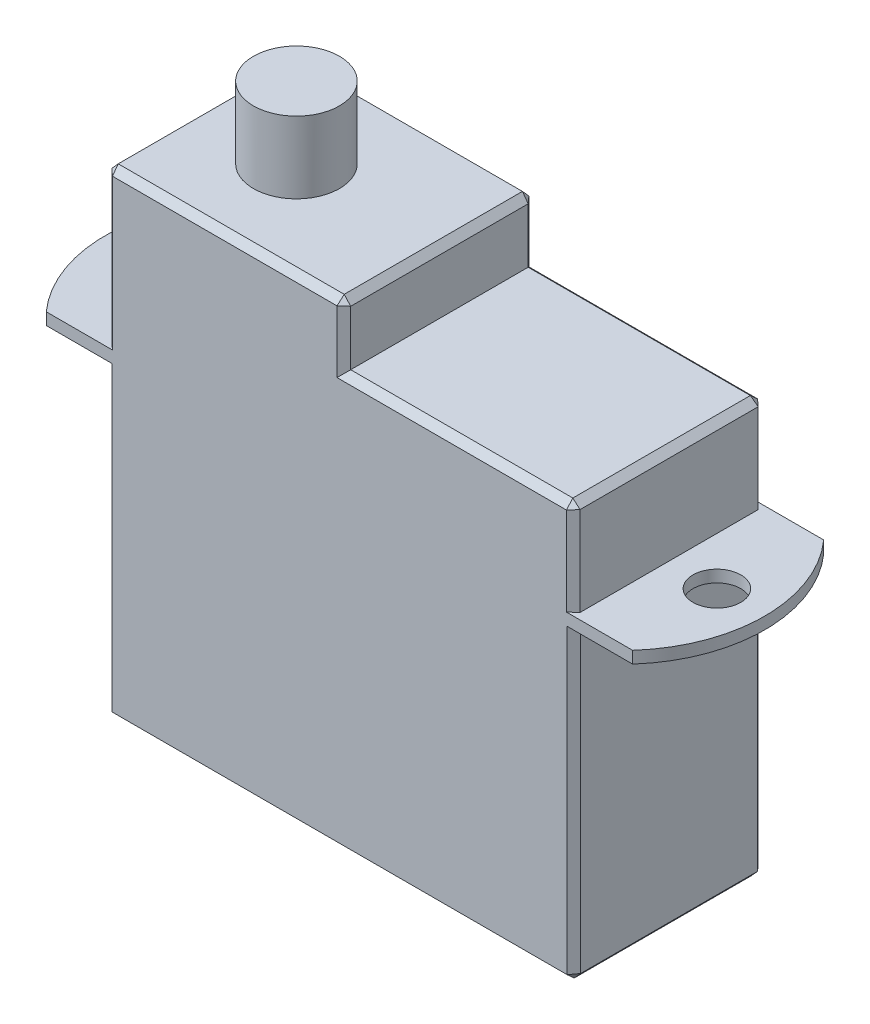
SolidWorks part; units mm, degrees
material "ABS"
ref_plane "前视基准面" through (0, 0, 0) normal (0, 0, 1) x (1, 0, 0)
ref_plane "上视基准面" through (0, 0, 0) normal (0, 1, 0) x (1, 0, 0)
ref_plane "右视基准面" through (0, 0, 0) normal (1, 0, 0) x (0, 0, -1)
sketch "草图1" plane through (0, 0, 0) normal (0, 1, 0) x (1, 0, 0)
  line L1 (-9.8, 4) -> (9.8, 4)
  line L2 (-9.8, 4) -> (-9.8, -4)
  line L3 (-9.8, -4) -> (9.8, -4)
  line L4 (9.8, 4) -> (9.8, -4)
  line L5 (-9.8, 4) -> (9.8, -4) construction
  line L6 (-9.8, -4) -> (9.8, 4) construction
  point P0 (0, 0)
extrude "凸台-拉伸1" add sketch "草图1" along normal blind 12.9
sketch "草图2" plane through (0, 12.9, 0) normal (0, 1, 0) x (1, 0, 0)
  line L1 (-13.8, 4) -> (13.8, 4)
  line L2 (-13.8, 4) -> (-13.8, -4)
  line L3 (-13.8, -4) -> (13.8, -4)
  line L4 (13.8, 4) -> (13.8, -4)
  line L5 (-13.8, 4) -> (13.8, -4) construction
  line L6 (-13.8, -4) -> (13.8, 4) construction
  circle A0 centre (-11.8, 0) radius 1
  circle A1 centre (11.8, 0) radius 1
  point P0 (0, 0)
  point P9 (0, 0)
extrude "凸台-拉伸2" add sketch "草图2" along normal blind 0.5
sketch "草图3" plane through (0, 0, 0) normal (0, -1, 0) x (1, 0, 0)
  line L4 (9.8, -4) -> (9.8, 4)
  line L5 (9.8, 4) -> (-9.8, 4)
  line L6 (-9.8, 4) -> (-9.8, -4)
  line L7 (-9.8, -4) -> (9.8, -4)
  line L8 (9.8, -4) -> (9.8, 4)
  line L9 (9.8, 4) -> (-9.8, 4)
  line L10 (-9.8, 4) -> (-9.8, -4)
  line L11 (-9.8, -4) -> (9.8, -4)
  dimension "D1" = 0
extrude "凸台-拉伸3" add sketch "草图3" against normal blind 17.4
sketch "草图4" plane through (0, 0, 0) normal (0, 1, 0) x (1, 0, 0)
  line L0 (-9.8, 4) -> (0.2, 4)
  line L1 (-9.8, 4) -> (9.8, 4) construction
  line L2 (0.2, 4) -> (0.2, -4)
  line L3 (9.8, -4) -> (-9.8, -4) construction
  line L4 (0.2, -4) -> (-9.8, -4)
  line L5 (-9.8, -4) -> (-9.8, 4)
extrude "凸台-拉伸5" add sketch "草图4" along normal blind 20
sketch "草图6" plane through (0, 20, 0) normal (0, 1, 0) x (1, 0, 0)
  circle A0 centre (-5.8, 0) radius 1.8
extrude "凸台-拉伸6" add sketch "草图6" along normal blind 3
sketch "草图7" plane through (0, 0, 0) normal (0, -1, 0) x (1, 0, 0)
  line L0 (14.367, -5.7855) -> (9.3898, -5.7855)
  line L2 (14.5401, 5.4875) -> (14.367, -5.7855)
  line L4 (-10.2264, 5.4875) -> (-14.5401, 5.4875)
  line L5 (-14.5401, 5.4875) -> (-14.367, -5.7855)
  line L6 (-14.367, -5.7855) -> (-9.3898, -5.7855)
  line L7 (0, 0) -> (0, 4.9525) construction
  line L8 (10.2264, 5.4875) -> (14.5401, 5.4875)
  arc A0 (-9.3898, -5.7855) -> (-10.2264, 5.4875) centre (-7.8, 0) cw
  arc A1 (9.3898, -5.7855) -> (10.2264, 5.4875) centre (7.8, 0) ccw
extrude "切除-拉伸2" cut sketch "草图7" against normal blind 17
chamfer "倒角1" distance 0.3 angle 42 21 edges at (0.2, 18.7, 4) (-4.8, 20, 4) (-9.8, 16.7, 4) (-9.8, 20, 0) (-9.8, 16.7, -4) (-4.8, 20, -4) (0.2, 20, 0) (0.2, 18.7, -4) (5, 17.4, -4) (5, 17.4, 4) (9.8, 15.4, -4) (9.8, 17.4, 0) (9.8, 15.4, 4) (0, 0, 4) (9.8, 6.45, 4) (9.8, 0, 0) (-9.8, 6.45, 4) (-9.8, 0, 0) (-9.8, 6.45, -4) (0, 0, -4) (9.8, 6.45, -4)
